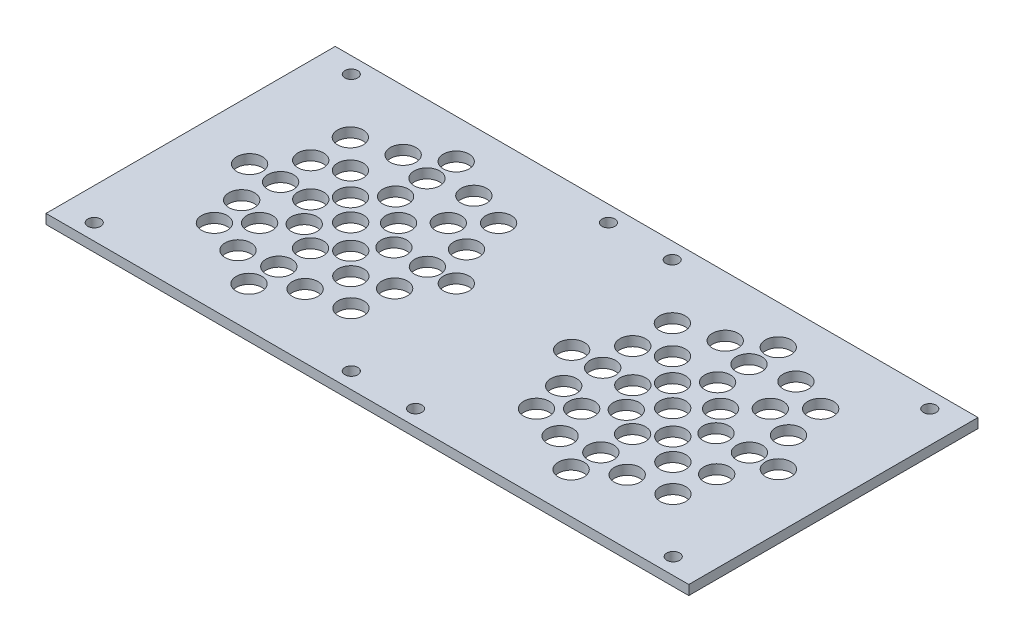
SolidWorks part; units mm, degrees
ref_plane "Front Plane" through (0, 0, 0) normal (0, 0, 1) x (1, 0, 0)
ref_plane "Top Plane" through (0, 0, 0) normal (0, 1, 0) x (1, 0, 0)
ref_plane "Right Plane" through (0, 0, 0) normal (1, 0, 0) x (0, 0, -1)
sketch "Sketch1" plane through (0, 0, 0) normal (0, 1, 0) x (1, 0, 0)
  line L1 (-93.1892, 52.9189) -> (106.8108, 52.9189)
  line L2 (-93.1892, 52.9189) -> (-93.1892, -37.0811)
  line L3 (-93.1892, -37.0811) -> (106.8108, -37.0811)
  line L4 (106.8108, 52.9189) -> (106.8108, -37.0811)
  dimension "D1" = 200
  dimension "D2" = 90
extrude "Boss-Extrude1" add sketch "Sketch1" along normal blind 3
sketch "Sketch2" plane through (0, 3, 0) normal (0, 1, 0) x (1, 0, 0)
  line L1 (6.8108, 63.729) -> (6.8108, -47.4814) construction
  circle A0 centre (-83.1892, 47.9189) radius 2
  circle A1 centre (-83.1892, -32.0811) radius 2
  circle A2 centre (-3.1892, 47.9189) radius 2
  circle A3 centre (-3.1892, -32.0811) radius 2
  circle A4 centre (96.9752, 47.7538) radius 2
  circle A5 centre (96.8907, -31.9998) radius 2
  circle A6 centre (16.731, 47.8377) radius 2
  circle A7 centre (16.9296, -32.2) radius 2
  circle A10 centre (64.4095, 15.2255) radius 4
  circle A11 centre (64.459, 0.3015) radius 4
  circle A12 centre (72.1506, 22.9576) radius 4
  circle A13 centre (79.9849, 30.783) radius 4
  circle A14 centre (42.7822, -6.3771) radius 4
  circle A15 centre (35.7447, -13.4064) radius 4
  circle A16 centre (50.0316, 0.2519) radius 4
  circle A17 centre (71.3287, -6.5407) radius 4
  circle A18 centre (56.8108, 7.9189) radius 4
  circle A19 centre (79.9849, -15.162) radius 4
  circle A20 centre (50.0316, 14.6709) radius 4
  circle A21 centre (42.7822, 21.8912) radius 4
  circle A22 centre (33.8545, 30.783) radius 4
  circle A23 centre (70.2869, 7.9189) radius 4
  circle A24 centre (80.6959, 7.9189) radius 4
  circle A25 centre (89.6983, 7.9189) radius 4
  circle A26 centre (35.0277, 7.9189) radius 4
  circle A27 centre (44.4051, 7.9189) radius 4
  circle A28 centre (25.3689, 7.9189) radius 4
  circle A29 centre (57.5336, -5.2808) radius 4
  circle A30 centre (57.5336, -15.162) radius 4
  circle A31 centre (57.5336, -24.4109) radius 4
  circle A32 centre (56.8108, 21.8912) radius 4
  circle A33 centre (56.8108, 31.6664) radius 4
  circle A34 centre (56.8108, 40.7625) radius 4
  circle A35 centre (33.8545, 18.4442) radius 4
  circle A36 centre (46.7822, 34.2921) radius 4
  circle A37 centre (68.7865, 34.2921) radius 4
  circle A38 centre (82.1025, 18.6709) radius 4
  circle A39 centre (81.4461, -3.0302) radius 4
  circle A40 centre (67.6612, -17.0964) radius 4
  circle A41 centre (46.7822, -17.0964) radius 4
  circle A42 centre (33.8545, -3.0302) radius 4
  circle A43 centre (-35.7614, 15.1877) radius 4
  circle A44 centre (-35.712, 0.2637) radius 4
  circle A45 centre (-28.0204, 22.9199) radius 4
  circle A46 centre (-20.186, 30.7452) radius 4
  circle A47 centre (-57.3888, -6.4148) radius 4
  circle A48 centre (-64.4262, -13.4442) radius 4
  circle A49 centre (-50.1393, 0.2141) radius 4
  circle A50 centre (-28.8422, -6.5784) radius 4
  circle A51 centre (-43.3601, 7.8811) radius 4
  circle A52 centre (-20.186, -15.1998) radius 4
  circle A53 centre (-50.1393, 14.6331) radius 4
  circle A54 centre (-57.3888, 21.8534) radius 4
  circle A55 centre (-66.3165, 30.7452) radius 4
  circle A56 centre (-29.884, 7.8811) radius 4
  circle A57 centre (-19.475, 7.8811) radius 4
  circle A58 centre (-10.4727, 7.8811) radius 4
  circle A59 centre (-65.1433, 7.8811) radius 4
  circle A60 centre (-55.7658, 7.8811) radius 4
  circle A61 centre (-74.8021, 7.8811) radius 4
  circle A62 centre (-42.6374, -5.3186) radius 4
  circle A63 centre (-42.6374, -15.1998) radius 4
  circle A64 centre (-42.6374, -24.4486) radius 4
  circle A65 centre (-43.3601, 21.8534) radius 4
  circle A66 centre (-43.3601, 31.6286) radius 4
  circle A67 centre (-43.3601, 40.7248) radius 4
  circle A68 centre (-66.3165, 18.4064) radius 4
  circle A69 centre (-53.3888, 34.2543) radius 4
  circle A70 centre (-31.3844, 34.2543) radius 4
  circle A71 centre (-18.0684, 18.6331) radius 4
  circle A72 centre (-18.7248, -3.068) radius 4
  circle A73 centre (-32.5097, -17.1342) radius 4
  circle A74 centre (-53.3888, -17.1342) radius 4
  circle A75 centre (-66.3165, -3.068) radius 4
  point P42 (71.3287, 7.9189)
  point P48 (89.6983, 7.9189)
  point P53 (0, 0)
  point P62 (42.7822, 7.9189)
  point P63 (32.4957, 7.9189)
  point P64 (23.3058, 7.9189)
  point P65 (44.4051, 7.9189)
  point P66 (35.0277, 7.9189)
  point P67 (25.3689, 7.9189)
  point P68 (70.2869, 7.9189)
  point P71 (56.8108, -6.3771)
  point P74 (56.8108, -16.7213)
  point P77 (57.5336, -26.005)
  point P78 (57.5336, -5.2808)
  point P79 (57.5336, -15.7836)
  point P80 (57.5336, -24.4109)
  point P81 (57.5336, -15.162)
  point P84 (56.8108, 22.9576)
  point P87 (56.8108, 32.6041)
  point P90 (56.8108, 40.7625)
  point P91 (56.8108, 31.6664)
  point P92 (56.8108, 21.8912)
  point P95 (33.8545, 18.4442)
  point P98 (46.7822, 34.2921)
  point P101 (68.7865, 34.2921)
  point P104 (82.1025, 19.2255)
  point P107 (81.4461, -3.0302)
  point P110 (67.6612, -17.0964)
  point P113 (46.7822, -17.0964)
  point P116 (33.8545, -3.0302)
extrude "Cut-Extrude1" cut sketch "Sketch2" against normal blind 3
